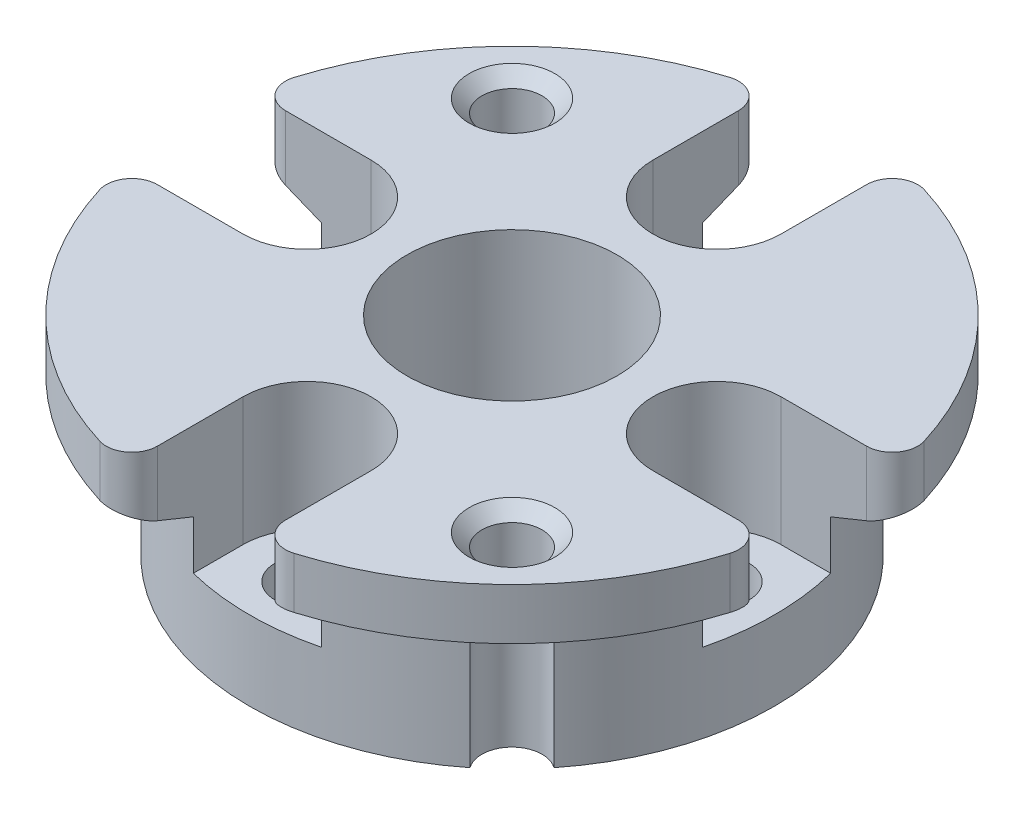
SolidWorks part; units mm, degrees
ref_plane "前视基准面" through (0, 0, 0) normal (0, 0, 1) x (1, 0, 0)
ref_plane "上视基准面" through (0, 0, 0) normal (0, 1, 0) x (1, 0, 0)
ref_plane "右视基准面" through (0, 0, 0) normal (1, 0, 0) x (0, 0, -1)
sketch "Sketch2" plane through (0, 0, 0) normal (0, 0, 1) x (1, 0, 0)
  line L0 (4.1, 0) -> (10.25, 0)
  line L1 (10.25, 0) -> (10.25, 5)
  line L5 (12.87, 6.09) -> (12.87, 8.09)
  line L6 (12.87, 8.09) -> (4.1, 8.09)
  line L7 (0, 8.09) -> (0, 0) construction
  line L8 (4.1, 0) -> (4.1, 8.09)
  line L9 (4.1, 8.09) -> (0, 8.09) construction
  line L10 (4.1, 8.09) -> (0, 8.09) construction
  line L11 (0, 0) -> (4.1, 0) construction
  line L12 (10.25, 5) -> (12.87, 6.09)
  point P4 (12.87, 4.7769)
  dimension "D1" = 8.09
  dimension "D2" = 10.25
  dimension "D3" = 12.87
  dimension "D4" = 4.1
  dimension "D5" = 5
  dimension "D6" = 2
revolve "Revolve2" add sketch "Sketch2" angle 360 about L7
sketch "Sketch3" plane through (0, 0, 0) normal (0, -1, 0) x (1, 0, 0)
  line L0 (0, 0) -> (0, 8)
  circle A0 centre (0, 8) radius 1.25
  circle A1 centre (8, 0) radius 1.25
  circle A2 centre (0, -8) radius 1.25
  circle A3 centre (-8, 0) radius 1.25
  point P13 (0, 0)
  dimension "D2" = 2.5
  dimension "D1" = 8
  dimension "D3" = 4
extrude "Cut-Extrude1" cut sketch "Sketch3" against normal through all
sketch "Sketch4" plane through (0, 8.09, 0) normal (0, 1, 0) x (1, 0, 0)
  line L0 (0, 0) -> (0, 8)
  line L1 (0, 0) -> (-7.3362, 7.3362)
  line L2 (0, 0) -> (7.3362, -7.3362) construction
  circle A0 centre (-7.3362, 7.3362) radius 1.175
  circle A1 centre (7.3362, -7.3362) radius 1.175
  point P10 (0, 0)
  dimension "D3" = 2.35
  dimension "D1" = 45
  dimension "D2" = 10.375
  dimension "D4" = 2
sketch "Sketch5" plane through (0, 8.09, 0) normal (0, 1, 0) x (1, 0, 0)
  line L0 (-2.5, -8) -> (-2.5, -14)
  line L1 (-2.5, -14) -> (2.5, -14)
  line L2 (2.5, -14) -> (2.5, -8)
  line L3 (-8, 2.5) -> (-14, 2.5)
  line L4 (-14, 2.5) -> (-14, -2.5)
  line L5 (-14, -2.5) -> (-8, -2.5)
  line L6 (2.5, 8) -> (2.5, 14)
  line L7 (2.5, 14) -> (-2.5, 14)
  line L8 (-2.5, 14) -> (-2.5, 8)
  line L9 (8, -2.5) -> (14, -2.5)
  line L10 (14, -2.5) -> (14, 2.5)
  line L11 (14, 2.5) -> (8, 2.5)
  arc A8 (2.5, -8) -> (-2.5, -8) centre (0, -8) ccw
  circle A12 centre (0, -8) radius 1.25 construction
  circle A16 centre (0, -8) radius 1.25 construction
  arc A20 (-2.5, -8) -> (2.5, -8) centre (0, -8) ccw construction
  arc A21 (-8, -2.5) -> (-8, 2.5) centre (-8, 0) ccw
  arc A22 (-2.5, 8) -> (2.5, 8) centre (0, 8) ccw
  arc A23 (8, 2.5) -> (8, -2.5) centre (8, 0) ccw
  point P25 (0, 0)
  dimension "D1" = 6
  dimension "D2" = 5
  dimension "D3" = 4
extrude "Cut-Extrude2" cut sketch "Sketch5" against normal blind 5
extrude "Cut-Extrude3" cut sketch "Sketch4" against normal through all
chamfer "Chamfer1" distance 0.5 angle 45 2 edges at (7.3362, 8.09, 8.5112) (-7.3362, 8.09, -6.1612)
fillet "Fillet1" radius 1 8 edges at (-2.5, 7.09, -12.6249) (2.5, 7.09, -12.6249) (-12.6249, 7.09, 2.5) (-12.6249, 7.09, -2.5) (12.6249, 7.09, -2.5) (12.6249, 7.09, 2.5) (2.5, 7.09, 12.6249) (-2.5, 7.09, 12.6249)
